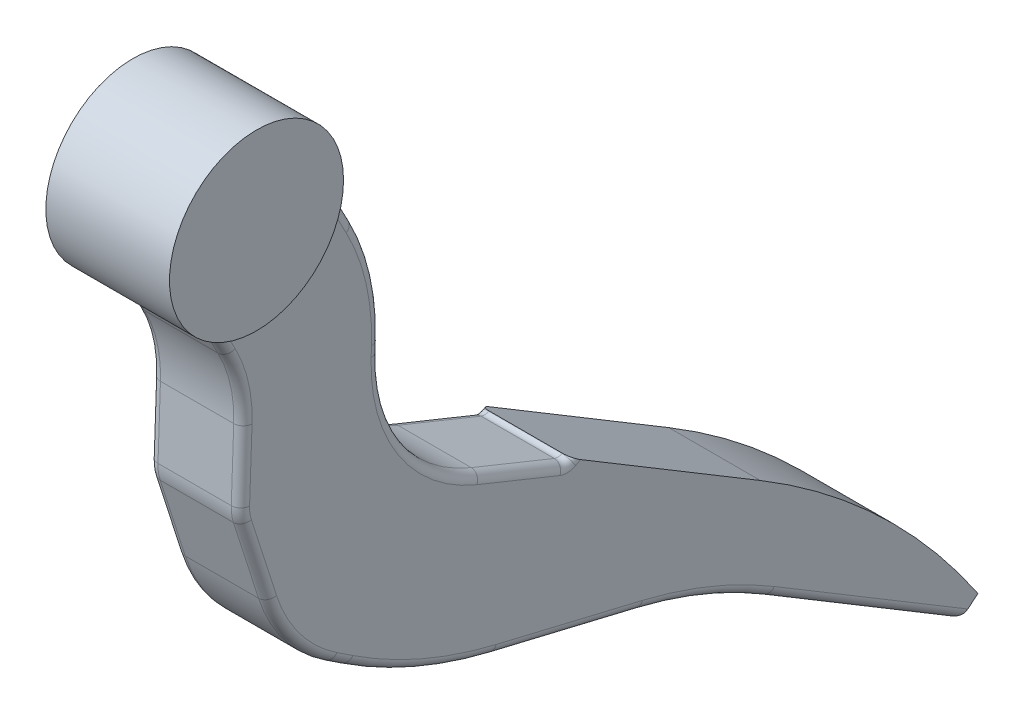
SolidWorks part; units mm, degrees
material "POM Acetal Copolymer"
ref_plane "Front" through (0, 0, 0) normal (0, 0, 1) x (1, 0, 0)
ref_plane "Top" through (0, 0, 0) normal (0, 1, 0) x (1, 0, 0)
ref_plane "Right" through (0, 0, 0) normal (1, 0, 0) x (0, 0, -1)
sketch "Sketch1" plane through (0, 0, 0) normal (1, 0, 0) x (0, 0, -1)
  circle A0 centre (0, 0) radius 19
  dimension "D1" = 38
extrude "Boss-Extrude1" add sketch "Sketch1" along normal blind 27
sketch "Sketch2" plane through (27, 0, 0) normal (1, 0, 0) x (0, 0, -1)
  circle A0 centre (0, 0) radius 3
  dimension "D1" = 6
extrude "Cut-Extrude1" cut sketch "Sketch2" along normal blind 20 from surface at -27 starting at face at (0, 0, -19)
sketch "Sketch3" plane through (0, 0, 0) normal (1, 0, 0) x (0, 0, -1)
  line L0 (18.8944, -2) -> (30.5718, -24.1052)
  line L1 (30.5718, -24.1052) -> (29.1601, -64.1052)
  line L2 (29.1601, -64.1052) -> (70.8771, -80.978)
  line L3 (70.8771, -80.978) -> (71.7613, -80.5109)
  line L4 (-6.6982, -17.7802) -> (0.3082, -31.0433)
  line L5 (0.3082, -31.0433) -> (-0.5741, -56.0433)
  line L6 (-0.5741, -56.0433) -> (9.2104, -86.5107)
  line L7 (9.2104, -86.5107) -> (37.6571, -105.2963)
  line L8 (37.6571, -105.2963) -> (101.784, -120.6205)
  line L9 (101.784, -120.6205) -> (156.6446, -153.5798)
  line L10 (156.6446, -153.5798) -> (160.5302, -150.4329)
  line L11 (71.7613, -80.5109) -> (113.0165, -105.2963)
  line L12 (18.8944, -2) -> (-6.6982, -17.7802)
  line L13 (-18.9799, 35.5401) -> (73.4131, -139.3603) construction
  line L14 (-41.5518, -50.7546) -> (128.7494, -119.6341) construction
  circle A0 centre (0, 0) radius 19 construction
  circle A1 centre (0, 0) radius 19 construction
  arc A2 (113.0165, -105.2963) -> (160.5302, -150.4329) centre (35.2564, -234.7276) cw
  dimension "D1" = 2
  dimension "D2" = 25
  dimension "D3" = 40
  dimension "D4" = 45
  dimension "D5" = 15
  dimension "D6" = 25
  dimension "D7" = 32
  dimension "D8" = 30
  dimension "D9" = 30
  dimension "D10" = 6.6982
  dimension "D11" = 1
  dimension "D12" = 220
  dimension "D13" = 5
  dimension "D14" = 30
  dimension "D15" = 160
  dimension "D16" = 35
  dimension "D17" = 113
  dimension "D18" = 110
  dimension "D19" = 19
  dimension "D20" = 110
  dimension "D21" = 64
extrude "Boss-Extrude2" add sketch "Sketch3" along normal blind 20 from offset 4
fillet "Fillet1" radius 50 1 edges at (14, -24.1052, -30.5718)
fillet "Fillet2" radius 30 1 edges at (14, -31.0433, -0.3082)
fillet "Fillet3" radius 10 1 edges at (14, -56.0433, 0.5741)
fillet "Fillet4" radius 35 1 edges at (14, -86.5107, -9.2104)
fillet "Fillet5" radius 100 2 edges at (14, -105.2963, -37.6571) (14, -120.6205, -101.784)
fillet "Fillet6" radius 35 1 edges at (14, -64.1052, -29.1601)
fillet "Fillet7" radius 2 1 edges at (14, -80.978, -70.8771)
fillet "Fillet8" radius 2 37 edges at (4, -141.0764, -135.8329) (4, -121.7178, -101.3358) (4, -113.2129, -70.7857) (4, -20.8744, 5.0636) (4, -31.2776, 0.7139) (4, -46.6682, 0.2432) (4, -56.0225, 0.4239) (4, -66.2485, -2.7033) (4, -85.2405, -10.8849) (4, -94.437, -21.2131) (24, -20.8744, 5.0636) (24, -31.2776, 0.7139) (24, -141.0764, -135.8329) (24, -121.7178, -101.3358) (24, -113.2129, -70.7857) (24, -103.8809, -38.2708) (24, -94.437, -21.2131) (24, -85.2405, -10.8849) (24, -66.2485, -2.7033) (24, -56.0225, 0.4239) (4, -7.157, -21.6187) (4, -24.4958, -28.8682) (4, -38.5227, -30.0629) (4, -80.5273, -71.7303) (4, -80.7727, -70.8667) (4, -76.9618, -60.9473) (24, -80.5273, -71.7303) (24, -80.7727, -70.8667) (24, -76.9618, -60.9473) (24, -7.157, -21.6187) (24, -24.4958, -28.8682) (24, -38.5227, -30.0629) (14, -153.5798, -156.6446) (4, -103.8809, -38.2708) (24, -46.6682, 0.2432) (4, -59.8991, -35.6422) (24, -59.8991, -35.6422)
